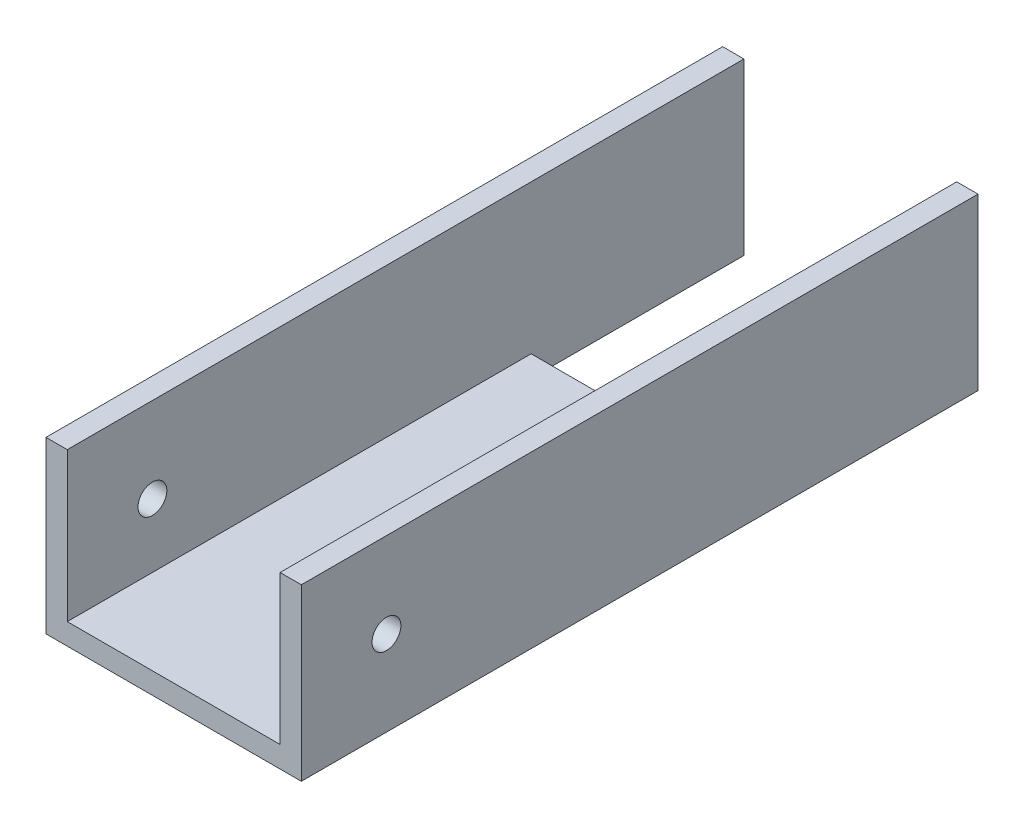
SolidWorks part; units mm, degrees
other "Markup1"
sketch "Sketch4" plane through (19.05, 12.7, 609.6) normal (0.165, 0.2552, 0.9527) x (0.9626, 0.1685, -0.2119)
ref_plane "Front" through (0, 0, 0) normal (0, 0, 1) x (1, 0, 0)
ref_plane "Top" through (0, 0, 0) normal (0, 1, 0) x (1, 0, 0)
ref_plane "Right" through (0, 0, 0) normal (1, 0, 0) x (0, 0, -1)
sketch "Sketch1" plane through (0, 0, 0) normal (0, 0, 1) x (1, 0, 0)
  line L0 (0, -12.7) -> (0, 12.7) construction
  line L1 (-19.05, 0) -> (19.05, 0) construction
  line L2 (15.875, 12.7) -> (-15.875, 12.7) construction
  line L3 (-19.05, -12.7) -> (19.05, -12.7)
  line L4 (-19.05, -12.7) -> (-19.05, 12.7)
  line L5 (-19.05, 12.7) -> (19.05, 12.7)
  line L6 (19.05, -12.7) -> (19.05, 12.7)
  line L7 (-19.05, -12.7) -> (19.05, 12.7) construction
  line L8 (-19.05, 12.7) -> (19.05, -12.7) construction
  line L9 (-15.875, -12.7) -> (15.875, -12.7)
  point P3 (0, 0)
  point P4 (0, 0)
  point P8 (0, 0)
  point P13 (19.05, -9.525)
  point P17 (0, 12.7)
  point P20 (0, -12.7)
  dimension "Outside Width" = 38.1
  dimension "Outside Height" = 25.4
  dimension "Inside Height" = 22.225
  dimension "Wall Thickness" = 3.175
  dimension "Inside Width" = 31.75
sketch "Sketch2" plane through (0, 0, 0) normal (1, 0, 0) x (0, 0, -1)
  line L0 (-609.6, 0) -> (609.6, 0) construction
  dimension "Length" = 1219.2
sketch "Sketch3" plane through (0, 0, 0) normal (0, 0, 1) x (1, 0, 0)
  line L0 (-19.05, 12.7) -> (-19.05, -12.7)
  line L1 (-19.05, -12.7) -> (19.05, -12.7)
  line L2 (19.05, -12.7) -> (19.05, 12.7)
  line L3 (19.05, 12.7) -> (15.875, 12.7)
  line L4 (15.875, 12.7) -> (15.875, -9.525)
  line L5 (15.875, -9.525) -> (-15.875, -9.525)
  line L6 (-15.875, -9.525) -> (-15.875, 12.7)
  line L7 (-15.875, 12.7) -> (-19.05, 12.7)
  line L8 (-15.875, -9.525) -> (-15.875, -12.7) construction
  dimension "D1" = 25.4
  dimension "D2" = 38.1
  dimension "D3" = 3.175
extrude "Boss-Extrude2" add sketch "Sketch3" along normal mid plane 1219.2
sketch "Reference Sketch1" plane through (0, 0, 0) normal (1, 0, 0) x (0, 0, -1)
  line L0 (-609.6, 0) -> (609.6, 0) construction
  point P0 (-565.15, 0)
  point P1 (565.15, 0)
  dimension "D1" = 44.45
  dimension "D2" = 44.45
sketch "Sketch5" plane through (0, 0, 609.6) normal (0, 0, 1) x (1, 0, 0)
  line L0 (-19.05, 12.7) -> (-15.875, 12.7)
  line L1 (-15.875, 12.7) -> (-15.875, -9.525)
  line L2 (-15.875, -9.525) -> (15.875, -9.525)
  line L3 (15.875, -9.525) -> (15.875, 12.7)
  line L4 (19.05, 12.7) -> (15.875, 12.7) construction
  line L5 (15.875, 12.7) -> (15.875, -9.525) construction
  line L6 (15.875, 12.7) -> (19.05, 12.7)
  line L7 (19.05, 12.7) -> (19.05, -12.7)
  line L8 (19.05, -12.7) -> (-19.05, -12.7)
  line L9 (-19.05, -12.7) -> (-19.05, 12.7)
extrude "Cut-Extrude1" cut sketch "Sketch5" against normal blind 1118.235
sketch "Sketch6" plane through (0, -12.7, 0) normal (0, -1, 0) x (1, 0, 0)
  line L0 (-19.05, -609.6) -> (19.05, -609.6) construction
  line L1 (15.875, -609.6) -> (-15.875, -609.6)
  line L2 (15.875, -609.6) -> (15.875, -577.85)
  line L3 (15.875, -577.85) -> (-15.875, -577.85)
  line L4 (-15.875, -609.6) -> (-15.875, -577.85)
  dimension "D1" = 31.75
extrude "Cut-Extrude2" cut sketch "Sketch6" against normal up to next
sketch "Sketch7" plane through (19.05, 0, 0) normal (1, 0, 0) x (0, 0, -1)
  line L0 (508.635, 12.7) -> (609.6, 12.7) construction
  line L2 (508.635, -12.7) -> (508.635, 12.7) construction
  point P0 (521.335, 0)
  dimension "D1" = 12.7
  dimension "D2" = 12.7
hole_wizard "#6 Clearance Hole1" positions "Sketch7" profile "Sketch8" hole size "#6" standard "ANSI Inch" end condition through all
sketch "Sketch8" plane through (19.05, 0, -521.335) normal (0, 1, 0) x (0, 0, -1)
  line L0 (0, 0) -> (0, 38.1)
  line L1 (0, 38.1) -> (2.1526, 38.1)
  line L2 (2.1526, 38.1) -> (2.1526, 0)
  line L5 (2.1526, 0) -> (0, 0)
  line L11 (0, -6.35) -> (0, 107.95) construction
  dimension "Thru Hole Dia." = 4.3053
  dimension "Thru Hole Depth" = 38.1
equation "\"D1@Sketch3\" = \"Outside Height@Sketch1\""
equation "\"D2@Sketch3\" = \"Outside Width@Sketch1\""
equation "\"D3@Sketch3\" = \"Wall Thickness@Sketch1\""
equation "\"D1@Reference Sketch1\"=\"Outside Height@Sketch1\" * 1.75"
equation "\"D2@Reference Sketch1\" = \"D1@Reference Sketch1\""
equation "\"D1@Boss-Extrude2\" = \"Length@Sketch2\""
equation "\"Inside Height@Sketch1\"=\"Outside Height@Sketch1\"-\"Wall Thickness@Sketch1\""
equation "\"Inside Width@Sketch1\"=\"Outside Width@Sketch1\"-\"Wall Thickness@Sketch1\"*2"
